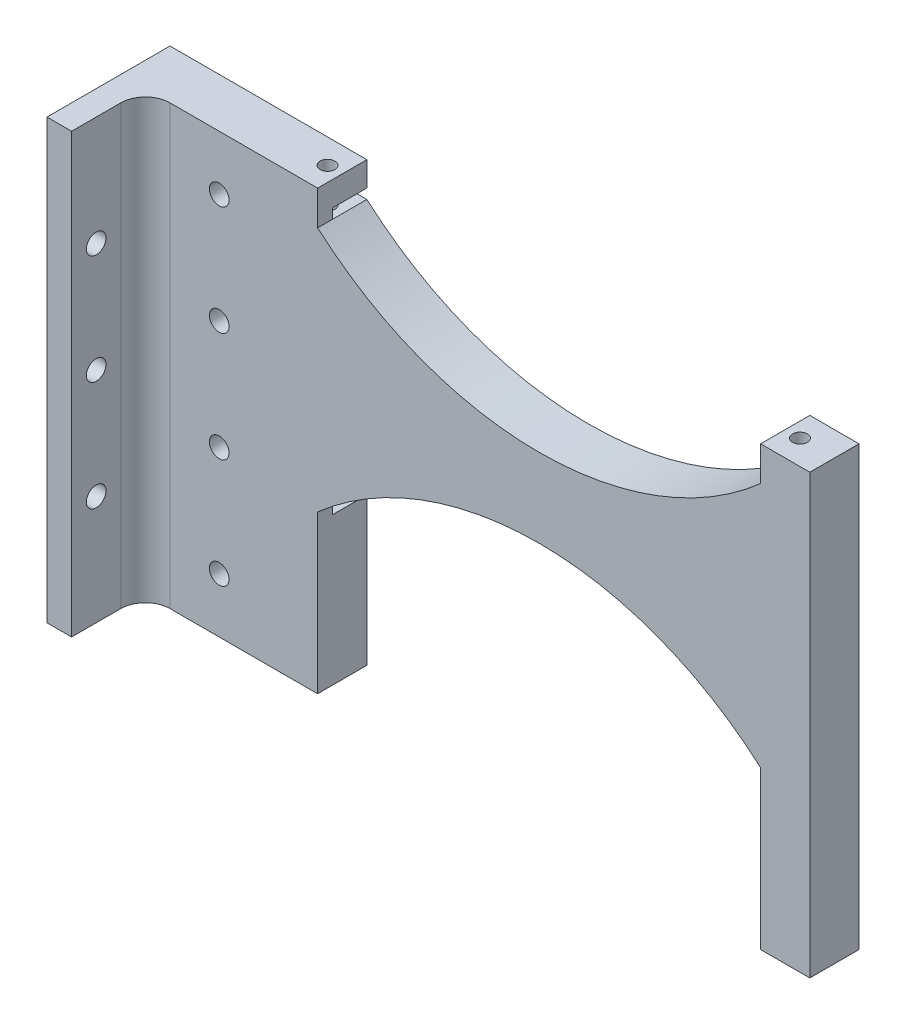
SolidWorks part; units mm, degrees
ref_plane "Front Plane" through (0, 0, 0) normal (0, 0, 1) x (1, 0, 0)
ref_plane "Top Plane" through (0, 0, 0) normal (0, 1, 0) x (1, 0, 0)
ref_plane "Right Plane" through (0, 0, 0) normal (1, 0, 0) x (0, 0, -1)
sketch "Sketch1" plane through (0, 0, 0) normal (0, 0, 1) x (1, 0, 0)
  line L1 (50, -25) -> (-50, -25)
  line L2 (50, -25) -> (50, 25)
  line L3 (50, 25) -> (-50, 25)
  line L4 (-50, -25) -> (-50, 25)
  line L5 (50, -25) -> (-50, 25) construction
  line L6 (50, 25) -> (-50, -25) construction
  arc A0 (-45, 25) -> (45, 25) centre (0, 76.0588) ccw
  arc A1 (-45.0185, -25) -> (45.0185, -25) centre (0, -76.1077) cw
  point P0 (0, 0)
  point P6 (-45, 25)
  point P7 (-45.0185, -25)
  point P8 (45, 25)
  point P9 (45.0185, -25)
  point P16 (0, -8)
  point P17 (0, 8)
  dimension "D1" = 50
  dimension "D2" = 100
  dimension "D3" = 5
  dimension "D4" = 5
  dimension "D5" = 8
  dimension "D6" = 8
extrude "Boss-Extrude1" add sketch "Sketch1" along normal blind 10 contours L1 A1 L2 L3 A0 L4
sketch "Sketch2" plane through (0, 25, 0) normal (0, 1, 0) x (1, 0, 0)
  line L0 (-50, -5) -> (50, -5) construction
  line L1 (-50, -10) -> (-50, 0) construction
  line L2 (50, -10) -> (50, 0) construction
  line L3 (-45, -10) -> (-45, 0) construction
  circle A0 centre (-48, -5) radius 1.5
  circle A1 centre (48, -5) radius 1.5
  point P7 (-48, -5)
  point P11 (48, -5)
  dimension "D2" = 96
  dimension "D3" = 3
extrude "Cut-Extrude1" cut sketch "Sketch2" against normal through all both and the other way through all
sketch "Sketch9" plane through (50, 0, 0) normal (1, 0, 0) x (0, 0, -1)
  line L1 (0, 25) -> (-10, 25)
  line L2 (0, 25) -> (0, -25)
  line L3 (0, -25) -> (-10, -25)
  line L4 (-10, 25) -> (-10, -25)
extrude "Boss-Extrude9" add sketch "Sketch9" along normal blind 5
sketch "Sketch10" plane through (-50, 0, 0) normal (-1, 0, 0) x (0, 0, 1)
  line L1 (10, -25) -> (0, -25)
  line L2 (10, -25) -> (10, 25)
  line L3 (10, 25) -> (0, 25)
  line L4 (0, -25) -> (0, 25)
extrude "Boss-Extrude10" add sketch "Sketch10" along normal blind 5
sketch "Sketch11" plane through (0, 25, 0) normal (0, 1, 0) x (1, 0, 0)
  line L0 (50, 0) -> (50, -7)
  line L1 (55, 0) -> (45, 0) construction
  line L2 (-50, 0) -> (-50, -7)
  line L3 (-45, 0) -> (-55, 0) construction
  line L4 (50, -7) -> (45, -7)
  line L5 (45, -10) -> (45, 0) construction
  line L6 (-50, -7) -> (-45, -7)
  line L7 (-45, -10) -> (-45, 0) construction
  line L8 (50, 0) -> (55, 0)
  line L9 (55, 0) -> (55, -10)
  line L10 (55, -10) -> (45, -10)
  line L11 (45, -10) -> (45, -7)
  line L12 (-45, -7) -> (-45, -10)
  line L13 (-45, -10) -> (-55, -10)
  line L14 (-55, -10) -> (-55, 0)
  line L15 (-55, 0) -> (-50, 0)
  circle A1 centre (48, -5) radius 1.5 construction
  circle A2 centre (-48, -5) radius 1.5 construction
  dimension "D1" = 100
  dimension "D2" = 2
  dimension "D3" = 2
extrude "Boss-Extrude11" add sketch "Sketch11" along normal blind 2
sketch "Sketch12" plane through (0, 27, 0) normal (0, 1, 0) x (1, 0, 0)
  line L0 (45, -7) -> (45, -10) construction
  line L1 (55, -10) -> (45, -10)
  line L2 (55, -10) -> (55, 0)
  line L3 (55, 0) -> (45, 0)
  line L4 (45, -10) -> (45, 0)
  line L6 (-55, -10) -> (-45, -10)
  line L7 (-55, -10) -> (-55, 0)
  line L8 (-55, 0) -> (-45, 0)
  line L9 (-45, -10) -> (-45, 0)
  dimension "D1" = 0
extrude "Boss-Extrude12" add sketch "Sketch12" along normal blind 5
sketch "Sketch13" plane through (0, 25, 0) normal (0, 1, 0) x (1, 0, 0)
  circle A0 centre (48, -5) radius 1.5
  circle A1 centre (-48, -5) radius 1.5
extrude "Cut-Extrude2" cut sketch "Sketch13" along normal up to surface (7 mm away) up to face at (-50, 32, 5)
sketch "Sketch14" plane through (0, -25, 0) normal (0, -1, 0) x (1, 0, 0)
  line L0 (50.0092, 0) -> (50.0092, 7)
  line L1 (55, 0) -> (45.0185, 0) construction
  line L2 (50.0092, 7) -> (45.0185, 7)
  line L3 (45.0185, 10) -> (45.0185, 0) construction
  line L4 (-50.0092, 0) -> (-50.0092, 7)
  line L5 (-45.0185, 0) -> (-55, 0) construction
  line L6 (-50.0092, 7) -> (-45.0185, 7)
  line L7 (-45.0185, 10) -> (-45.0185, 0) construction
  line L8 (-45.0185, 7) -> (-45.0185, 10)
  line L9 (-45.0185, 10) -> (-55, 10)
  line L10 (-55, 10) -> (-55, 0)
  line L11 (-55, 0) -> (-50.0092, 0)
  line L12 (45.0185, 7) -> (45.0185, 10)
  line L13 (45.0185, 10) -> (55, 10)
  line L14 (55, 10) -> (55, 0)
  line L15 (55, 0) -> (50.0092, 0)
  circle A0 centre (48, 5) radius 1.5 construction
  dimension "D1" = 2
extrude "Boss-Extrude13" add sketch "Sketch14" along normal blind 2
sketch "Sketch15" plane through (0, -27, 0) normal (0, -1, 0) x (1, 0, 0)
  line L1 (-55, 0) -> (-45.0185, 0)
  line L2 (-55, 0) -> (-55, 10)
  line L3 (-55, 10) -> (-45.0185, 10)
  line L4 (-45.0185, 0) -> (-45.0185, 10)
  line L5 (55, 10) -> (45.0185, 10)
  line L6 (55, 10) -> (55, 0)
  line L7 (55, 0) -> (45.0185, 0)
  line L8 (45.0185, 10) -> (45.0185, 0)
extrude "Boss-Extrude14" add sketch "Sketch15" along normal blind 30
sketch "Sketch16" plane through (0, -25, 0) normal (0, -1, 0) x (1, 0, 0)
  circle A1 centre (48, 5) radius 1.5
  circle A3 centre (-48, 5) radius 1.5
extrude "Cut-Extrude3" cut sketch "Sketch16" along normal up to surface (32 mm away) up to face at (-50.0092, -57, 5)
sketch "Sketch17" plane through (-55, 0, 0) normal (-1, 0, 0) x (0, 0, 1)
  line L1 (0, 32) -> (10, 32)
  line L2 (0, 32) -> (0, -57)
  line L3 (0, -57) -> (10, -57)
  line L4 (10, 32) -> (10, -57)
extrude "Boss-Extrude15" add sketch "Sketch17" along normal blind 30
sketch "Sketch19" plane through (0, 0, 10) normal (0, 0, 1) x (1, 0, 0)
  line L0 (-45.0185, -57) -> (-85, -57) construction
  line L1 (-85, 32) -> (-80, 32)
  line L2 (-85, 32) -> (-85, -57)
  line L3 (-85, -57) -> (-80, -57)
  line L4 (-80, 32) -> (-80, -57)
  dimension "D1" = 5
extrude "Boss-Extrude16" add sketch "Sketch19" along normal blind 15
fillet "Fillet1" radius 5 1 edges at (-80, -12.5, 10)
sketch "Sketch20" plane through (-80, 0, 0) normal (1, 0, 0) x (0, 0, -1)
  line L0 (-15, 32) -> (-25, 32) construction
  circle A0 centre (-20, 9.75) radius 2
  circle A1 centre (-20, -12.5) radius 2
  circle A2 centre (-20, -34.75) radius 2
  point P9 (-20, 9.75)
  point P10 (-20, -12.5)
  point P11 (-20, -34.75)
extrude "Cut-Extrude4" cut sketch "Sketch20" against normal through all
sketch "Sketch21" plane through (0, 0, 10) normal (0, 0, 1) x (1, 0, 0)
  line L0 (-65, -34.75) -> (-65, -57) construction
  line L4 (-45.0185, -57) -> (-75, -57) construction
  line L6 (-65, 32) -> (-65, 9.75) construction
  line L7 (-75, 32) -> (-45, 32) construction
  line L8 (-65, 9.75) -> (-65, -12.5) construction
  line L9 (-65, -12.5) -> (-65, -34.75) construction
  circle A0 centre (-65, 20.875) radius 2
  circle A1 centre (-65, -1.375) radius 2
  circle A2 centre (-65, -23.625) radius 2
  circle A3 centre (-65, -45.875) radius 2
  point P1 (-65, -34.75)
  point P7 (-65, 9.75)
  point P8 (-65, -12.5)
  point P11 (-65, 20.875)
  point P13 (-65, -1.375)
  point P14 (-65, -23.625)
  point P15 (-65, -45.875)
extrude "Cut-Extrude5" cut sketch "Sketch21" against normal blind 10
